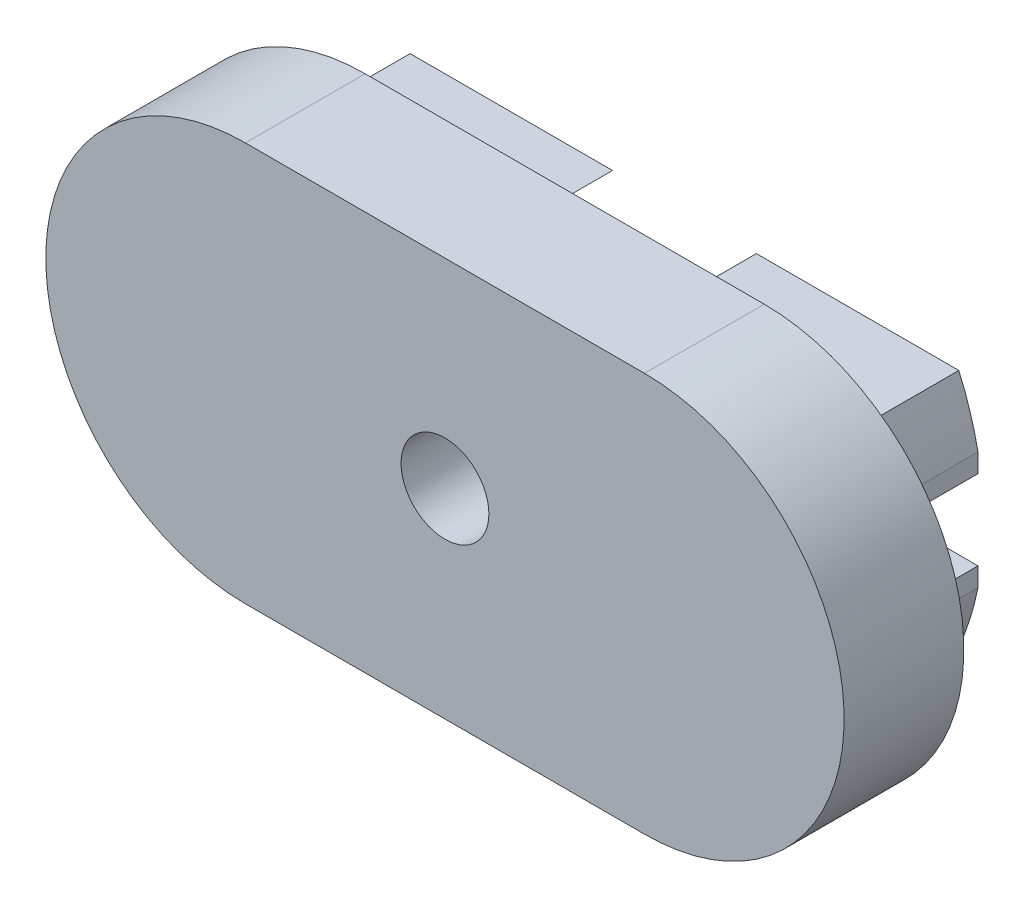
SolidWorks part; units mm, degrees
ref_plane "前视基准面" through (0, 0, 0) normal (0, 0, 1) x (1, 0, 0)
ref_plane "上视基准面" through (0, 0, 0) normal (0, 1, 0) x (1, 0, 0)
ref_plane "右视基准面" through (0, 0, 0) normal (1, 0, 0) x (0, 0, -1)
other "Configuration Table"
sketch "草图1" plane through (0, 0, 0) normal (0, 0, 1) x (1, 0, 0)
  line L0 (-5, 0) -> (5, 0) construction
  line L1 (-5, 5) -> (5, 5)
  line L2 (-5, -5) -> (5, -5)
  circle A0 centre (0, 0) radius 1.1
  arc A1 (-5, 5) -> (-5, -5) centre (-5, 0) ccw
  arc A2 (5, -5) -> (5, 5) centre (5, 0) ccw
  point P5 (0, 0)
  point P10 (0, 0)
  dimension "D1" = 2.2
  dimension "D2" = 10
  dimension "D3" = 10
extrude "凸台-拉伸1" add sketch "草图1" along normal blind 3
sketch "草图3" plane through (0, 0, 0) normal (0, 0, -1) x (-1, 0, 0)
  line L0 (-1.8028, 3) -> (-6.8739, 3)
  line L1 (-3.3541, 1) -> (-7.3541, 1)
  line L5 (-7.3541, 1.4721) -> (-7.3541, 1)
  line L6 (-7.3541, 0) -> (0, 0) construction
  line L7 (0, 0) -> (0, 5) construction
  line L8 (-5, 5) -> (5, 5) construction
  line L9 (-7.3541, -1.4721) -> (-7.3541, -1)
  line L10 (-3.3541, -1) -> (-7.3541, -1)
  line L11 (-1.8028, -3) -> (-6.8739, -3)
  line L12 (1.8028, -3) -> (6.8739, -3)
  line L13 (3.3541, -1) -> (7.3541, -1)
  line L14 (7.3541, -1.4721) -> (7.3541, -1)
  line L15 (7.3541, 1.4721) -> (7.3541, 1)
  line L16 (3.3541, 1) -> (7.3541, 1)
  line L17 (1.8028, 3) -> (6.8739, 3)
  arc A0 (-1.8028, 3) -> (-3.3541, 1) centre (0, 0) ccw
  arc A1 (-1.8028, -3) -> (-3.3541, -1) centre (0, 0) cw
  arc A2 (1.8028, -3) -> (3.3541, -1) centre (0, 0) ccw
  arc A3 (1.8028, 3) -> (3.3541, 1) centre (0, 0) cw
  arc A4 (-6.8739, 3) -> (-7.3541, 1.4721) centre (0, 0) ccw
  arc A5 (-7.3541, -1.4721) -> (-6.8739, -3) centre (0, 0) ccw
  arc A6 (6.8739, -3) -> (7.3541, -1.4721) centre (0, 0) ccw
  arc A7 (7.3541, 1.4721) -> (6.8739, 3) centre (0, 0) ccw
  dimension "D1" = 7
  dimension "D5" = 15
  dimension "D2" = 1
  dimension "D3" = 4
  dimension "D4" = 3
extrude "凸台-拉伸2" add sketch "草图3" along normal blind 3
